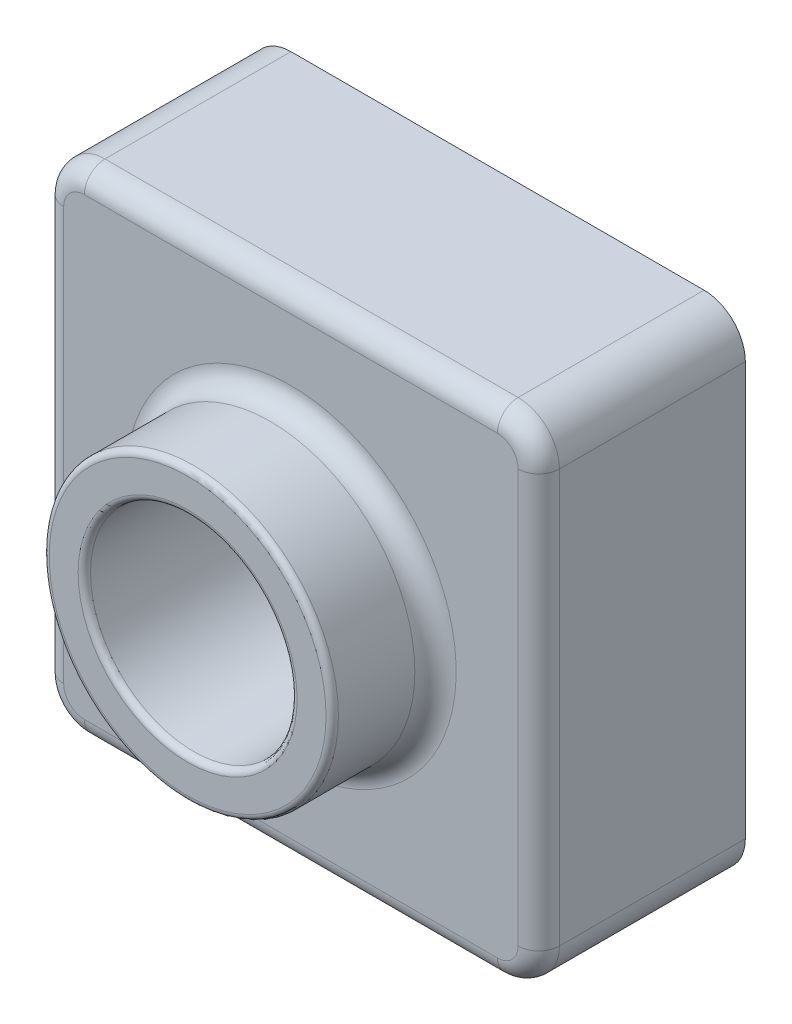
SolidWorks part; units mm, degrees
material "橡木"
ref_plane "前视基准面" through (0, 0, 0) normal (0, 0, 1) x (1, 0, 0)
ref_plane "上视基准面" through (0, 0, 0) normal (0, 1, 0) x (1, 0, 0)
ref_plane "右视基准面" through (0, 0, 0) normal (1, 0, 0) x (0, 0, -1)
sketch "草图1" plane through (0, 0, 0) normal (0, 0, 1) x (1, 0, 0)
  line L1 (0, 0) -> (120, 0)
  line L2 (0, 0) -> (0, 120)
  line L3 (0, 120) -> (120, 120)
  line L4 (120, 0) -> (120, 120)
  dimension "D1" = 120
  dimension "D2" = 120
extrude "凸台-拉伸1" add sketch "草图1" along normal blind 50
sketch "草图2" plane through (0, 0, 50) normal (0, 0, 1) x (1, 0, 0)
  line L0 (120, 120) -> (0, 120) construction
  line L1 (120, 0) -> (120, 120) construction
  circle A0 centre (60, 60) radius 35
  dimension "D1" = 70
  dimension "D2" = 60
  dimension "D3" = 60
extrude "凸台-拉伸2" add sketch "草图2" along normal blind 25
sketch "草图3" plane through (0, 0, 75) normal (0, 0, 1) x (1, 0, 0)
  circle A0 centre (60, 60) radius 25
  dimension "D1" = 50
extrude "切除-拉伸1" cut sketch "草图3" against normal through all
fillet "圆角1" radius 10 4 edges at (0, 120, 25) (0, 0, 25) (120, 0, 25) (120, 120, 25)
fillet "圆角2" radius 1.5 2 edges at (95, 60, 75) (85, 60, 75)
fillet "圆角3" radius 5 9 edges at (117.0711, 117.0711, 50) (120, 60, 50) (117.0711, 2.9289, 50) (60, 0, 50) (2.9289, 2.9289, 50) (0, 60, 50) (2.9289, 117.0711, 50) (60, 120, 50) (95, 60, 50)
shell "抽壳1" thickness 2
